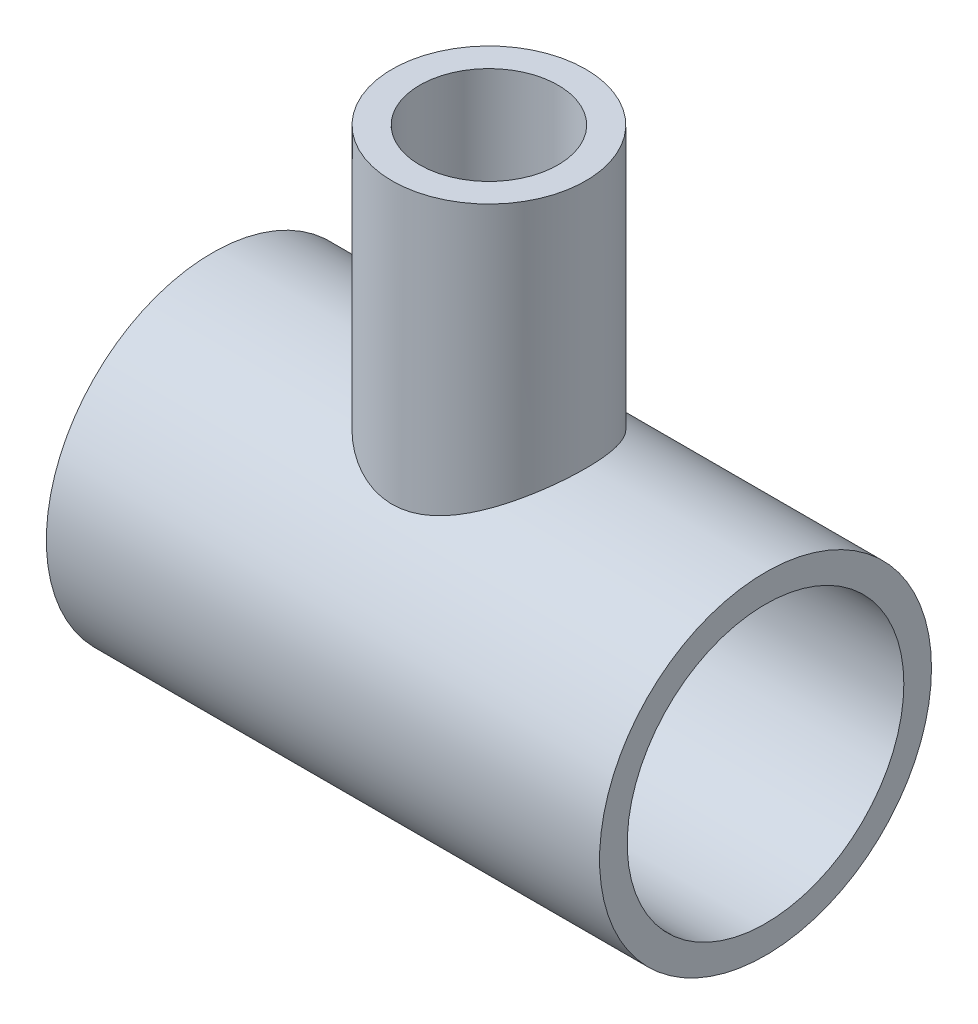
SolidWorks part; units mm, degrees
material "Nylon 101"
ref_plane "Front Plane" through (0, 0, 0) normal (0, 0, 1) x (1, 0, 0)
ref_plane "Top Plane" through (0, 0, 0) normal (0, 1, 0) x (1, 0, 0)
ref_plane "Right Plane" through (0, 0, 0) normal (1, 0, 0) x (0, 0, -1)
sketch "Sketch1" plane through (0, 0, 0) normal (1, 0, 0) x (0, 0, -1)
  circle A0 centre (0, 0) radius 7.62
  dimension "D2" = 15.24
extrude "Boss-Extrude1" add sketch "Sketch1" along normal blind 25.4
sketch "Sketch2" plane through (0, 0, 0) normal (0, 1, 0) x (1, 0, 0)
  circle A1 centre (12.7, 0) radius 4.445
  dimension "D3" = 8.89
  dimension "D1" = 12.7
extrude "Boss-Extrude2" add sketch "Sketch2" along normal blind 19.05
sketch "Sketch3" plane through (25.4, 0, 0) normal (1, 0, 0) x (0, 0, -1)
  circle A0 centre (0, 0) radius 6.35
  dimension "D1" = 12.7
extrude "Cut-Extrude1" cut sketch "Sketch3" against normal through all
sketch "Sketch4" plane through (0, 19.05, 0) normal (0, 1, 0) x (1, 0, 0)
  circle A0 centre (12.7, 0) radius 3.175
  dimension "D1" = 6.35
extrude "Cut-Extrude2" cut sketch "Sketch4" against normal up to next
